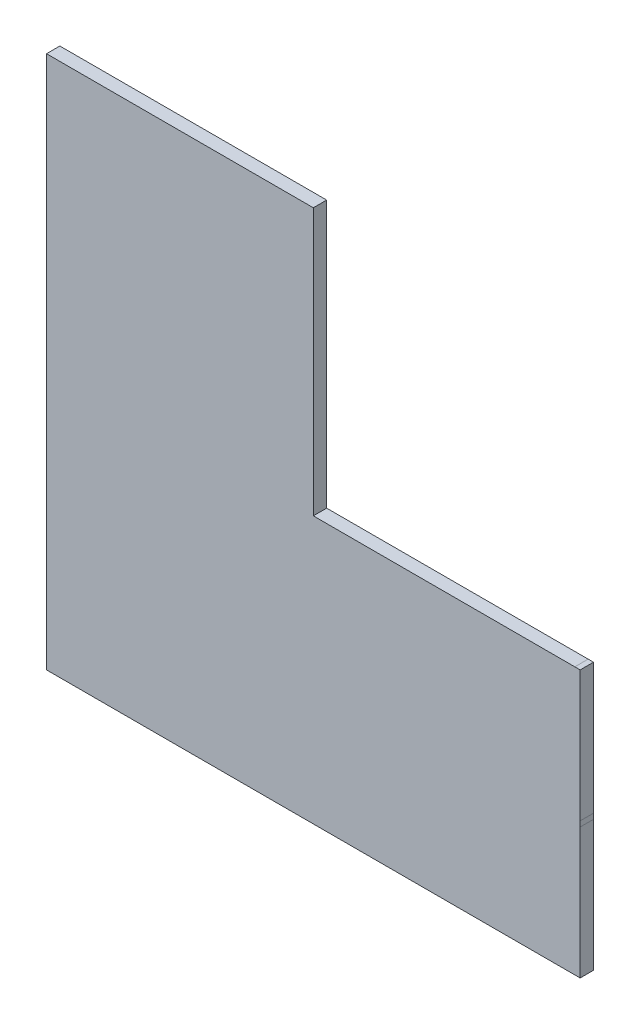
SolidWorks part; units mm, degrees
ref_plane "Front Plane" through (0, 0, 0) normal (0, 0, 1) x (1, 0, 0)
ref_plane "Top Plane" through (0, 0, 0) normal (0, 1, 0) x (1, 0, 0)
ref_plane "Right Plane" through (0, 0, 0) normal (1, 0, 0) x (0, 0, -1)
sketch "Sketch1" plane through (0, 0, 0) normal (0, 0, 1) x (1, 0, 0)
  line L0 (0, 0) -> (1000, 0)
  line L1 (1000, 0) -> (1000, 500)
  line L2 (1000, 500) -> (500, 500)
  line L3 (500, 500) -> (500, 1000)
  line L4 (500, 1000) -> (0, 1000)
  line L5 (0, 1000) -> (0, 0)
  dimension "D1" = 1000
  dimension "D2" = 500
  dimension "D3" = 500
  dimension "D4" = 1000
extrude "Boss-Extrude1" add sketch "Sketch1" along normal blind 25
sketch "Sketch3" plane through (1000, 0, 0) normal (1, 0, 0) x (0, 0, -1)
  line L1 (-25, 0) -> (-25, 500) construction
  line L2 (0, 0) -> (0, 500) construction
  line L4 (-25, 255) -> (0, 255)
  line L5 (-25, 245) -> (0, 245)
  line L6 (-25, 0) -> (0, 0) construction
  dimension "D2" = 10
  dimension "D3" = 245
split line "Split Line1"
sketch "Sketch4" plane through (0, 500, 0) normal (0, 1, 0) x (1, 0, 0)
  line L0 (990, 0) -> (990, -25)
  line L1 (1000, 0) -> (500, 0) construction
  line L2 (1000, -25) -> (500, -25) construction
  line L3 (1000, -25) -> (1000, 0) construction
  dimension "D1" = 10
split line "Split Line2"
